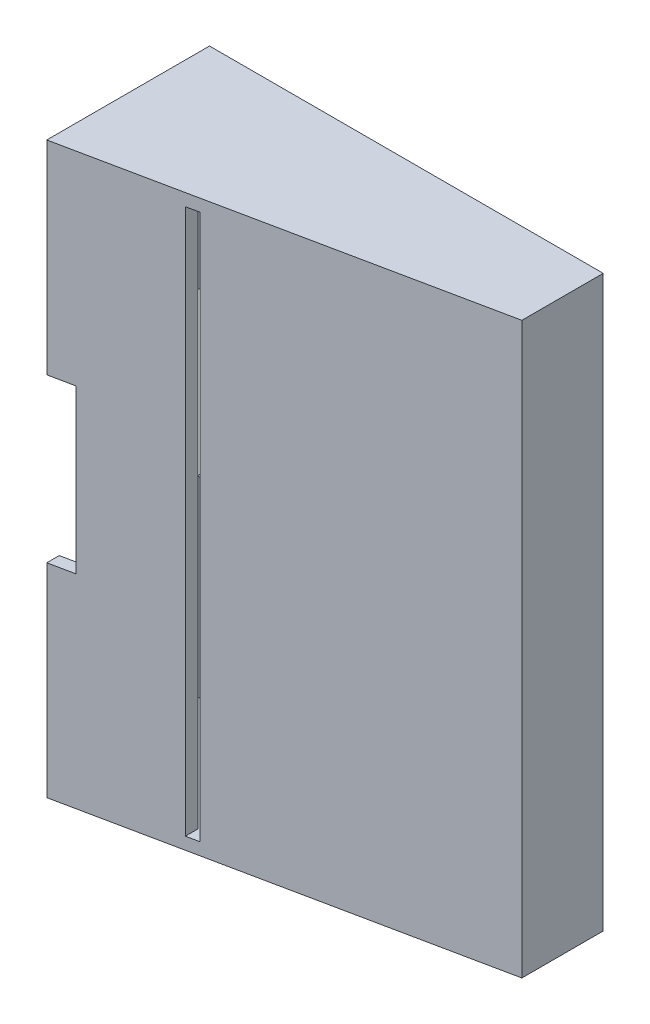
SolidWorks part; units mm, degrees
ref_plane "Front Plane" through (0, 0, 0) normal (0, 0, 1) x (1, 0, 0)
ref_plane "Top Plane" through (0, 0, 0) normal (0, 1, 0) x (1, 0, 0)
ref_plane "Right Plane" through (0, 0, 0) normal (1, 0, 0) x (0, 0, -1)
sketch "Sketch1" plane through (0, 0, 0) normal (0, 0, 1) x (1, 0, 0)
  line L3 (-46.8875, 15.35) -> (-46.8875, 35.15)
  line L32 (-43.9875, 35.15) -> (-46.8875, 35.15)
  line L33 (-43.9875, 15.35) -> (-43.9875, 35.15)
  line L34 (-46.8875, 15.35) -> (-43.9875, 15.35)
  line L35 (-43.9875, 35.15) -> (-46.8875, 35.15)
  line L36 (-43.9875, 15.35) -> (-43.9875, 35.15)
  line L37 (-46.8875, 15.35) -> (-43.9875, 15.35)
  dimension "D1" = 0.1
extrude "Boss-Extrude1" add sketch "Sketch1" against normal up to surface (1.5 mm away)
sketch "Sketch2" plane through (0, 0, -1.5) normal (0, 0, -1) x (-1, 0, 0)
  line L0 (24.3875, 19.15) -> (24.3875, 31.35) construction
  line L1 (46.8875, 12.35) -> (24.3875, 12.35)
  line L2 (46.8875, 12.35) -> (46.8875, 38.15)
  line L3 (46.8875, 38.15) -> (24.3875, 38.15)
  line L4 (24.3875, 12.35) -> (24.3875, 38.15)
  line L5 (46.8875, 12.35) -> (24.3875, 38.15) construction
  line L6 (46.8875, 38.15) -> (24.3875, 12.35) construction
  line L7 (43.9875, 35.15) -> (46.8875, 35.15) construction
  line L12 (24.3875, 25.25) -> (46.8875, 25.25) construction
  line L13 (46.8875, 35.15) -> (46.8875, 15.35) construction
  line L14 (46.8875, -9.75) -> (46.8875, 60.25) construction
  point P0 (35.6375, 25.25)
  dimension "D1" = 3
extrude "Boss-Extrude3" add sketch "Sketch2" along normal blind 1.5
sketch "Sketch3" plane through (0, 0, 0) normal (0, 0, 1) x (1, 0, 0)
  line L0 (-46.8875, 15.25) -> (-46.8875, 35.25)
  line L8 (-43.8875, 15.25) -> (-46.8875, 15.25)
  line L9 (-43.8875, 15.25) -> (-46.8875, 15.25)
  line L10 (-46.8875, 15.25) -> (-46.8875, -9.75)
  line L11 (-46.8875, -9.75) -> (1.5, -9.75)
  line L12 (1.5, -9.75) -> (1.5, 60.25)
  line L13 (1.5, 60.25) -> (-46.8875, 60.25)
  line L14 (-46.8875, 60.25) -> (-46.8875, 35.25)
  line L15 (-46.8875, 35.25) -> (-43.8875, 35.25)
  line L18 (-46.8875, 15.25) -> (-46.8875, -9.75)
  line L19 (-46.8875, -9.75) -> (1.5, -9.75)
  line L20 (1.5, -9.75) -> (1.5, 60.25)
  line L21 (1.5, 60.25) -> (-46.8875, 60.25)
  line L22 (-46.8875, 60.25) -> (-46.8875, 35.25)
  line L94 (-46.8875, 35.25) -> (-43.8875, 35.25)
  line L95 (-43.8875, 35.25) -> (-43.8875, 15.25)
  line L96 (-43.8875, 35.25) -> (-43.8875, 15.25)
  dimension "D1" = 0
extrude "Boss-Extrude4" add sketch "Sketch3" along normal blind 20 contours L94 L96 L9 L18 L19 L20 L21 L22
sketch "Sketch4" plane through (0, -9.75, 0) normal (0, -1, 0) x (1, 0, 0)
  line L0 (-46.8875, 20) -> (1.5, 10)
  line L1 (1.5, 10) -> (1.5, 20)
  line L2 (1.5, 20) -> (-46.8875, 20)
  line L3 (1.5, 20) -> (1.5, 0) construction
  line L4 (-46.8875, 20) -> (1.5, 20) construction
  point P3 (0, 0)
  point P4 (1.5, 20)
  point P7 (0, 0)
  point P12 (-46.8875, 20)
  point P15 (-40.5951, 20)
  point P17 (0, 0)
  line M2 (1.5, 0) -> (1.5, 20)
  line M9 (1.5, 20) -> (-46.8875, 20)
  dimension "D1" = 10
extrude "Cut-Extrude1" cut sketch "Sketch4" against normal up to next (70 mm away) contours L0 M9 M2
ref_plane "Plane1" through (0, 25.25, 0) normal (0, 1, 0) x (1, 0, 0)
sketch "Sketch5" plane through (0, -9.75, 0) normal (0, -1, 0) x (1, 0, 0)
  line L4 (-46.8875, 20) -> (-46.8875, 0) construction
  line L5 (-45.3875, 1.5) -> (0, 1.5)
  line L6 (-46.8875, 1.5) -> (0, 1.5)
  line L7 (0, 8.7783) -> (-45.3875, 18.1583)
  line L8 (0, 1.5) -> (0, 8.7783)
  line L9 (0, 8.7783) -> (-46.8875, 18.4683)
  line L10 (-45.3875, 18.1583) -> (-45.3875, 1.5)
  line L12 (0, 1.5) -> (0, 8.7783)
  line L14 (-46.8875, 18.4683) -> (-46.8875, 1.5)
  point P1 (-46.6839, 18.4683)
  point P8 (-46.6199, 1.5)
  line M7 (-46.8875, 20) -> (-46.8875, 0)
  dimension "D1" = 1.5
extrude "Cut-Extrude2" cut sketch "Sketch5" along normal up to surface (33.5 mm away) from offset 1.5 contours L6 L12 L9 M7
mirror "Mirror1" about plane through (0, 25.25, 0) normal (0, 1, 0) of "Cut-Extrude2"
sketch "Sketch6" plane through (0, 0, 1.5) normal (0, 0, -1) x (-1, 0, 0)
  line L0 (11, 25.25) -> (-11, 25.25) construction
  line L1 (32.77, 58.75) -> (31.27, 58.75)
  line L2 (32.77, 58.75) -> (32.77, -8.25)
  line L3 (32.77, -8.25) -> (31.27, -8.25)
  line L4 (31.27, 58.75) -> (31.27, -8.25)
  line L5 (32.77, 58.75) -> (31.27, -8.25) construction
  line L6 (32.77, -8.25) -> (31.27, 58.75) construction
  line L7 (39.5375, 58.75) -> (0, 58.75) construction
  line L10 (0, 58.75) -> (0, -8.25) construction
  point P0 (32.02, 25.25)
  line M15 (46.8875, -8.25) -> (0, -8.25)
  line M17 (0, 58.75) -> (46.8875, 58.75)
  dimension "D1" = 1.5
  dimension "D2" = 31.27
extrude "Cut-Extrude3" cut sketch "Sketch6" against normal up to surface and the other way up to surface (1.5 mm away) contours L4 L2 M17 M15 up to face at (-34.0406, 25.25, 17.345) other way up to face at (-34.0406, 25.25, 0)
